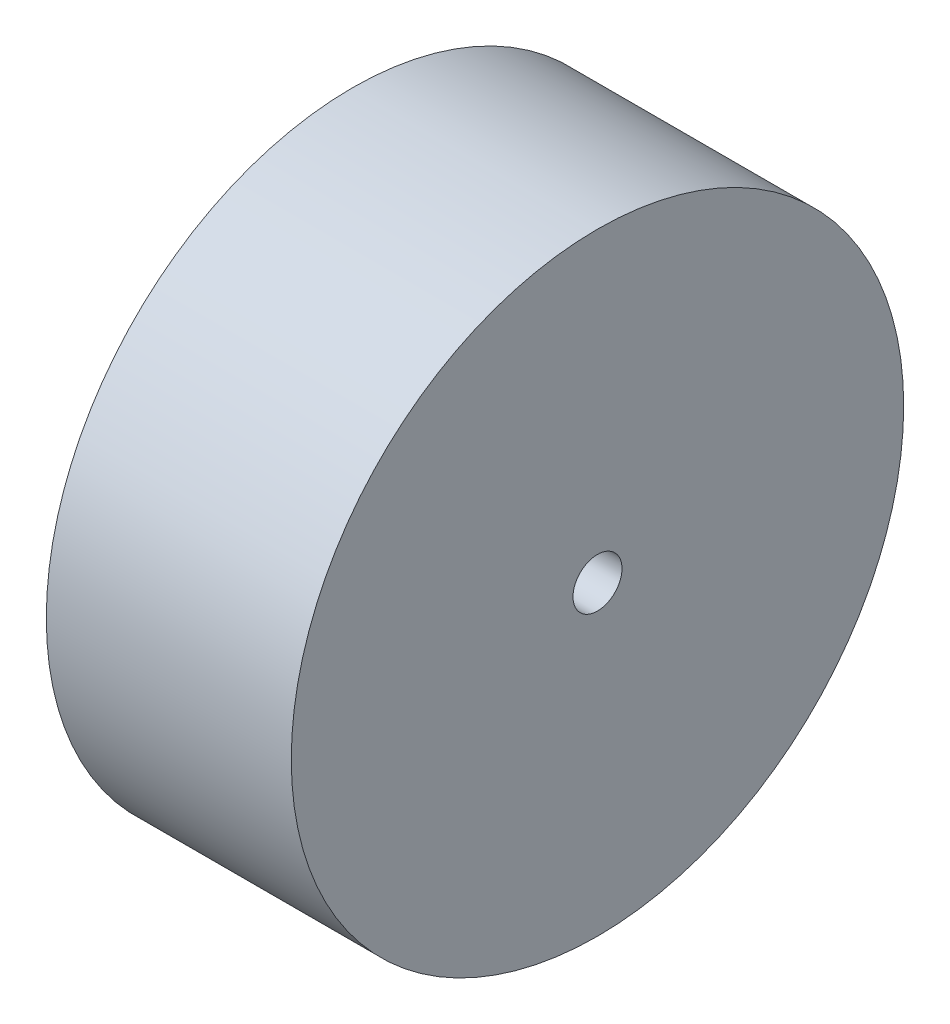
SolidWorks part; units mm, degrees
ref_plane "Front" through (0, 0, 0) normal (0, 0, 1) x (1, 0, 0)
ref_plane "Top" through (0, 0, 0) normal (0, 1, 0) x (1, 0, 0)
ref_plane "Right" through (0, 0, 0) normal (1, 0, 0) x (0, 0, -1)
sketch "Sketch1" plane through (0, 0, 0) normal (1, 0, 0) x (0, 0, -1)
  circle A0 centre (0, 0) radius 62.5
  circle A1 centre (0, 0) radius 5
  dimension "D1" = 10
  dimension "D2" = 125
extrude "Boss-Extrude1" add sketch "Sketch1" along normal blind 50
